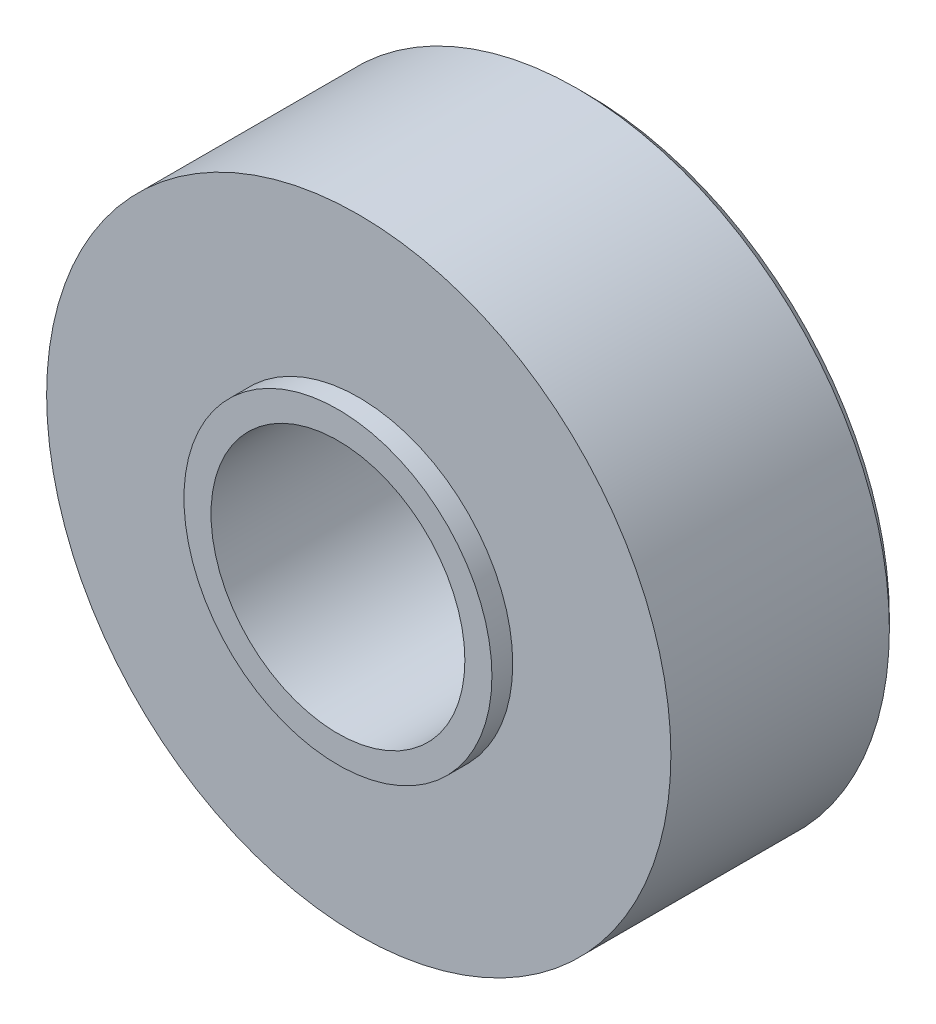
SolidWorks part; units mm, degrees
ref_plane "Front Plane" through (0, 0, 0) normal (0, 0, 1) x (1, 0, 0)
ref_plane "Top Plane" through (0, 0, 0) normal (0, 1, 0) x (1, 0, 0)
ref_plane "Right Plane" through (0, 0, 0) normal (1, 0, 0) x (0, 0, -1)
sketch "Sketch1" plane through (0, 0, 0) normal (0, 0, 1) x (1, 0, 0)
  circle A0 centre (0, 0) radius 7.5
  circle A1 centre (0, 0) radius 3.05
  dimension "D1" = 15
  dimension "D2" = 6.1
extrude "Boss-Extrude1" add sketch "Sketch1" along normal blind 5.5
sketch "Sketch2" plane through (0, 0, 5.5) normal (0, 0, 1) x (1, 0, 0)
  circle A0 centre (0, 0) radius 3.7
  circle A1 centre (0, 0) radius 3.05
  dimension "D1" = 7.4
  dimension "D2" = 6.1
extrude "Boss-Extrude2" add sketch "Sketch2" along direction (0, 0, 1) on the side of the normal blind 0.5
chamfer "Chamfer1" distance 0.25 angle 45 2 edges at (3.05, 0, 0) (7.5, 0, 0)
